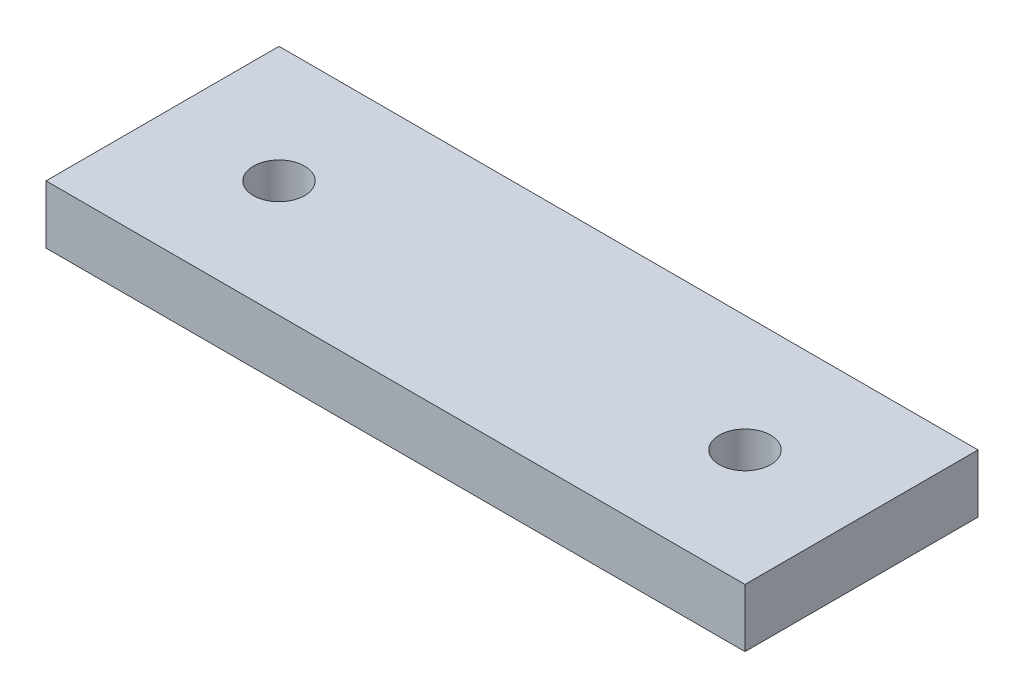
SolidWorks part; units mm, degrees
ref_plane "Front" through (0, 0, 0) normal (0, 0, 1) x (1, 0, 0)
ref_plane "Top" through (0, 0, 0) normal (0, 1, 0) x (1, 0, 0)
ref_plane "Right" through (0, 0, 0) normal (1, 0, 0) x (0, 0, -1)
sketch "Sketch1" plane through (0, 0, 0) normal (0, 1, 0) x (1, 0, 0)
  line L1 (0, 0) -> (76.2, 0)
  line L2 (0, 0) -> (0, 25.4)
  line L3 (0, 25.4) -> (76.2, 25.4)
  line L4 (76.2, 0) -> (76.2, 25.4)
  circle A0 centre (63.5, 12.7) radius 2.794
  circle A1 centre (12.7, 12.7) radius 2.794
  point P9 (0, 0)
  point P10 (0, 0)
  dimension "D3" = 5.588
  dimension "D4" = 5.588
  dimension "D1" = 76.2
  dimension "D2" = 25.4
  dimension "D5" = 12.7
  dimension "D6" = 12.7
  dimension "D7" = 12.7
  dimension "D8" = 12.7
extrude "Boss-Extrude1" add sketch "Sketch1" along normal blind 6.35
